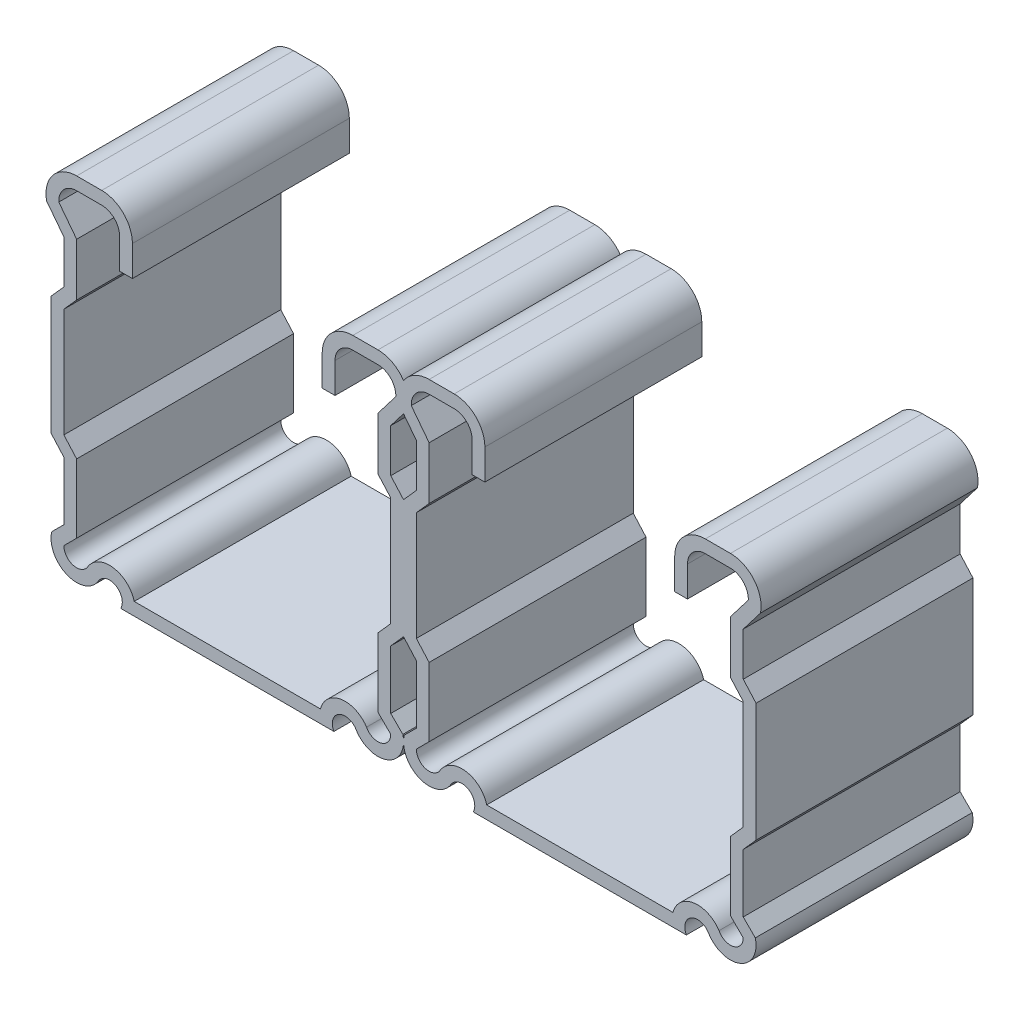
SolidWorks part; units mm, degrees
ref_plane "Plane1" through (0, 0, 0) normal (0, 0, 1) x (1, 0, 0)
ref_plane "Plane2" through (0, 0, 0) normal (0, 1, 0) x (1, 0, 0)
ref_plane "Plane3" through (0, 0, 0) normal (1, 0, 0) x (0, 0, -1)
sketch "Sketch1" plane through (0, 0, 0) normal (0, 0, 1) x (1, 0, 0)
  line L0 (17.6403, 16.3393) -> (19.7299, 19.0635)
  line L1 (17.6403, -13.9795) -> (19.1389, -15.4781)
  line L2 (-17.6403, -13.9795) -> (-19.1389, -15.4781)
  line L4 (-17.6403, -13.9795) -> (-17.6403, -5.9368)
  line L5 (17.6403, 21.2598) -> (14.7033, 21.2598)
  line L6 (12.6111, 19.1676) -> (12.6111, 15.6147)
  line L7 (-17.6403, -5.9368) -> (-19.1389, -4.2539)
  line L8 (-12.6111, 19.1676) -> (-12.6111, 15.6147)
  line L9 (0, 10.16) -> (0, -7.62) construction
  line L10 (-19.1389, -4.2539) -> (-19.1389, 8.4957)
  line L11 (-17.6403, 10.1786) -> (-19.1389, 8.4957)
  line L12 (-17.6403, 10.1786) -> (-17.6403, 16.3393)
  line L13 (-17.6403, 16.3393) -> (-19.7299, 19.0635)
  line L14 (-17.6403, 21.2598) -> (-14.7033, 21.2598)
  line L16 (17.6403, -13.9795) -> (17.6403, -5.9368)
  line L17 (17.6403, 10.1786) -> (17.6403, 16.3393)
  line L18 (-11.1125, 19.1676) -> (-11.1125, 15.6147)
  line L19 (-17.6403, 22.7584) -> (-14.7033, 22.7584)
  line L20 (-19.1389, 15.8307) -> (-21.1624, 18.4689)
  line L21 (-19.1389, 10.7491) -> (-19.1389, 15.8307)
  line L22 (-19.1389, 10.7491) -> (-20.6375, 9.0662)
  line L23 (-20.6375, -4.8244) -> (-20.6375, 9.0662)
  line L24 (-19.1389, -6.5073) -> (-20.6375, -4.8244)
  line L25 (19.1389, -4.2539) -> (19.1389, 8.4957)
  line L26 (-19.1389, -13.3588) -> (-19.1389, -6.5073)
  line L27 (-19.1389, -13.3588) -> (-20.5535, -14.7733)
  line L28 (11.1125, 19.1676) -> (11.1125, 15.6147)
  line L29 (17.6403, 22.7584) -> (14.7033, 22.7584)
  line L30 (19.1389, 15.8307) -> (21.1624, 18.4689)
  line L31 (19.1389, 10.7491) -> (19.1389, 15.8307)
  line L32 (19.1389, 10.7491) -> (20.6375, 9.0662)
  line L33 (20.6375, -4.8244) -> (20.6375, 9.0662)
  line L34 (19.1389, -6.5073) -> (20.6375, -4.8244)
  line L35 (19.1389, -13.3588) -> (19.1389, -6.5073)
  line L36 (19.1389, -13.3588) -> (20.5535, -14.7733)
  line L37 (17.6403, -5.9368) -> (19.1389, -4.2539)
  line L38 (-12.4806, -18.5166) -> (12.4806, -18.5166)
  line L39 (17.6403, 10.1786) -> (19.1389, 8.4957)
  line L41 (-10.899, -17.018) -> (10.899, -17.018)
  line L42 (-12.6111, 15.6147) -> (-11.1125, 15.6147)
  line L43 (11.1125, 15.6147) -> (12.6111, 15.6147)
  arc A0 (19.1389, -15.4781) -> (16.3052, -16.1588) centre (17.6403, -15.4781) cw
  arc A1 (16.3052, -16.1588) -> (10.899, -17.018) centre (13.7938, -17.7947) ccw
  arc A2 (-16.4143, -16.3399) -> (-10.899, -17.018) centre (-13.7938, -17.7947) cw
  arc A3 (-19.1389, -15.4781) -> (-16.4143, -16.3399) centre (-17.6403, -15.4781) ccw
  arc A4 (-17.6403, 21.2598) -> (-19.7299, 19.0635) centre (-17.6403, 19.1676) ccw
  arc A5 (-12.6111, 19.1676) -> (-14.7033, 21.2598) centre (-14.7033, 19.1676) ccw
  arc A6 (17.6403, 21.2598) -> (19.7299, 19.0635) centre (17.6403, 19.1676) cw
  arc A7 (12.6111, 19.1676) -> (14.7033, 21.2598) centre (14.7033, 19.1676) cw
  arc A8 (-11.1125, 19.1676) -> (-14.7033, 22.7584) centre (-14.7033, 19.1676) ccw
  arc A9 (-17.6403, 22.7584) -> (-21.1624, 18.4689) centre (-17.6403, 19.1676) ccw
  arc A10 (-20.5535, -14.7733) -> (-15.0198, -16.9329) centre (-17.6403, -15.4781) ccw
  arc A11 (11.1125, 19.1676) -> (14.7033, 22.7584) centre (14.7033, 19.1676) cw
  arc A12 (17.6403, 22.7584) -> (21.1624, 18.4689) centre (17.6403, 19.1676) cw
  arc A13 (20.5535, -14.7733) -> (15.0198, -16.9329) centre (17.6403, -15.4781) cw
  arc A14 (15.0198, -16.9329) -> (12.4806, -18.5166) centre (13.7938, -17.7947) ccw
  arc A15 (-15.0198, -16.9329) -> (-12.4806, -18.5166) centre (-13.7938, -17.7947) cw
  dimension "D9" = 7.1437
  dimension "base" = 18.5166
  dimension "D5" = 9.525
  dimension "ToeHt" = 22.7584
  dimension "D6" = 22.225
  dimension "D8" = 15.4781
  dimension "D12" = 41.275
  dimension "D14" = 13.6922
  dimension "D15" = 13.8906
extrude "Base-Extrude" add sketch "Sketch1" along normal mid plane 25.4
pattern_linear "LPattern2" count 2 spacing 41.2725 along (1, 0, 0) of "Base-Extrude"
